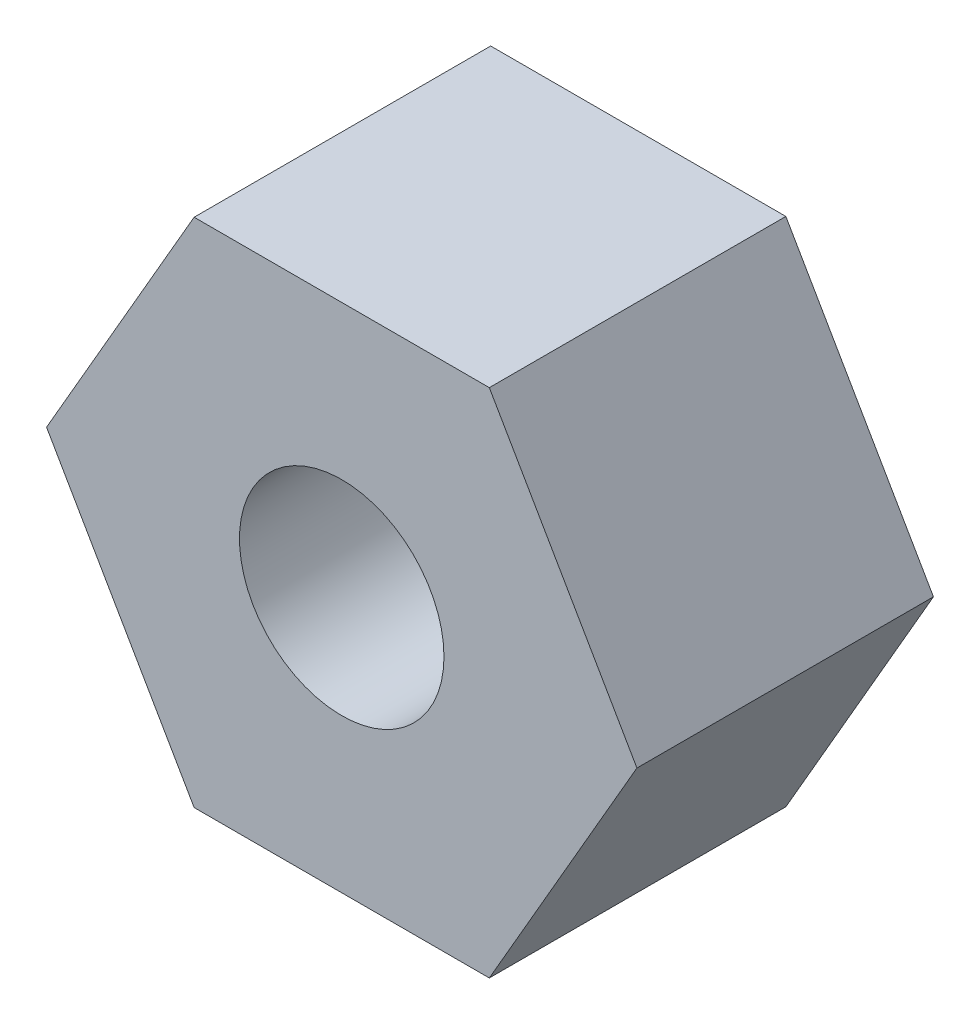
SolidWorks part; units mm, degrees
ref_plane "前视基准面" through (0, 0, 0) normal (0, 0, 1) x (1, 0, 0)
ref_plane "上视基准面" through (0, 0, 0) normal (0, 1, 0) x (1, 0, 0)
ref_plane "右视基准面" through (0, 0, 0) normal (1, 0, 0) x (0, 0, -1)
sketch "草图1" plane through (0, 0, 0) normal (0, 0, 1) x (1, 0, 0)
  line L1 (2.8868, -5) -> (5.7735, 0)
  line L2 (5.7735, 0) -> (2.8868, 5)
  line L3 (2.8868, 5) -> (-2.8868, 5)
  line L4 (-2.8868, 5) -> (-5.7735, 0)
  line L5 (-5.7735, 0) -> (-2.8868, -5)
  line L6 (-2.8868, -5) -> (2.8868, -5)
  circle A0 centre (0, 0) radius 2
  circle A1 centre (0, 0) radius 5 construction
  dimension "D1" = 4
  dimension "D2" = 10
extrude "凸台-拉伸1" add sketch "草图1" along normal blind 5.8
